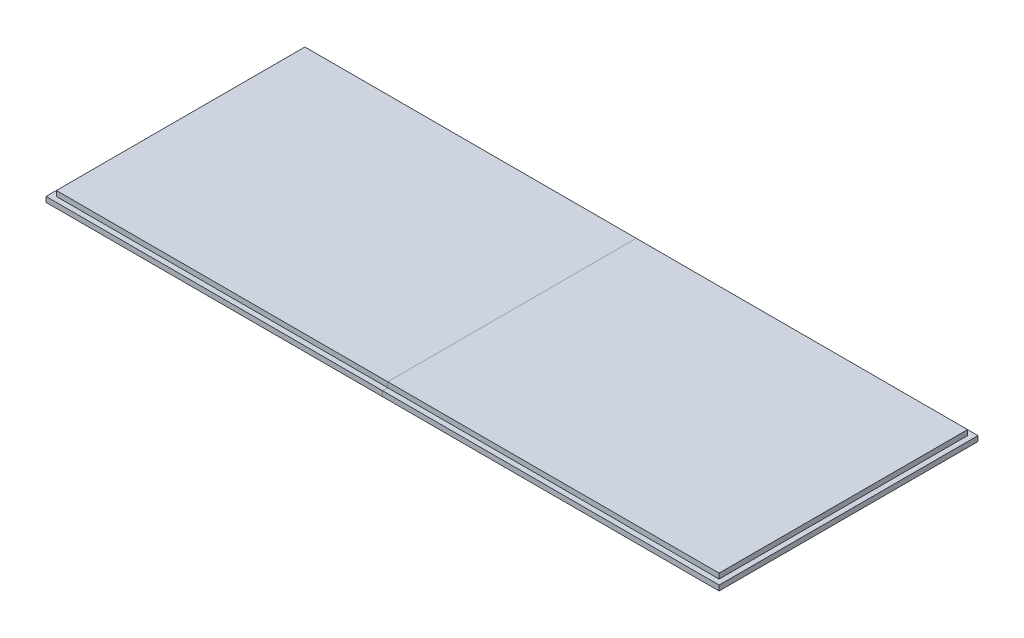
SolidWorks part; units mm, degrees
ref_plane "Front Plane" through (0, 0, 0) normal (0, 0, 1) x (1, 0, 0)
ref_plane "Top Plane" through (0, 0, 0) normal (0, 1, 0) x (1, 0, 0)
ref_plane "Right Plane" through (0, 0, 0) normal (1, 0, 0) x (0, 0, -1)
sketch "Sketch1" plane through (0, 0, 0) normal (0, 1, 0) x (1, 0, 0)
  line L1 (-203.2, -76.2) -> (203.2, -76.2)
  line L2 (-203.2, -76.2) -> (-203.2, 76.2)
  line L3 (-203.2, 76.2) -> (203.2, 76.2)
  line L4 (203.2, -76.2) -> (203.2, 76.2)
  line L5 (-203.2, -76.2) -> (203.2, 76.2) construction
  line L6 (-203.2, 76.2) -> (203.2, -76.2) construction
  line L7 (-206.375, -79.375) -> (206.375, -79.375)
  line L8 (-206.375, -79.375) -> (-206.375, 79.375)
  line L9 (-206.375, 79.375) -> (206.375, 79.375)
  line L10 (206.375, -79.375) -> (206.375, 79.375)
  line L11 (-206.375, -79.375) -> (206.375, 79.375) construction
  line L12 (-206.375, 79.375) -> (206.375, -79.375) construction
  point P0 (0, 0)
  point P6 (0, 0)
  dimension "D1" = 152.4
  dimension "D2" = 406.4
  dimension "D3" = 412.75
  dimension "D4" = 158.75
sketch "Sketch2" plane through (0, 0, 0) normal (0, 1, 0) x (1, 0, 0)
  line L1 (-203.2, -76.2) -> (203.2, -76.2)
  line L2 (-203.2, -76.2) -> (-203.2, 76.2)
  line L3 (-203.2, 76.2) -> (203.2, 76.2)
  line L4 (203.2, -76.2) -> (203.2, 76.2)
  line L5 (-203.2, -76.2) -> (203.2, 76.2) construction
  line L6 (-203.2, 76.2) -> (203.2, -76.2) construction
  point P0 (0, 0)
extrude "Boss-Extrude3" add sketch "Sketch1" along normal blind 3.175
ref_plane "Plane1" through (0, 0, 0) normal (1, 0, 0) x (0, 0, -1)
extrude "Boss-Extrude5" add sketch "Sketch2" along normal blind 6.35
split "Split1" trim tools "Plane1" bodies to split 105 resulting bodies 106 107
